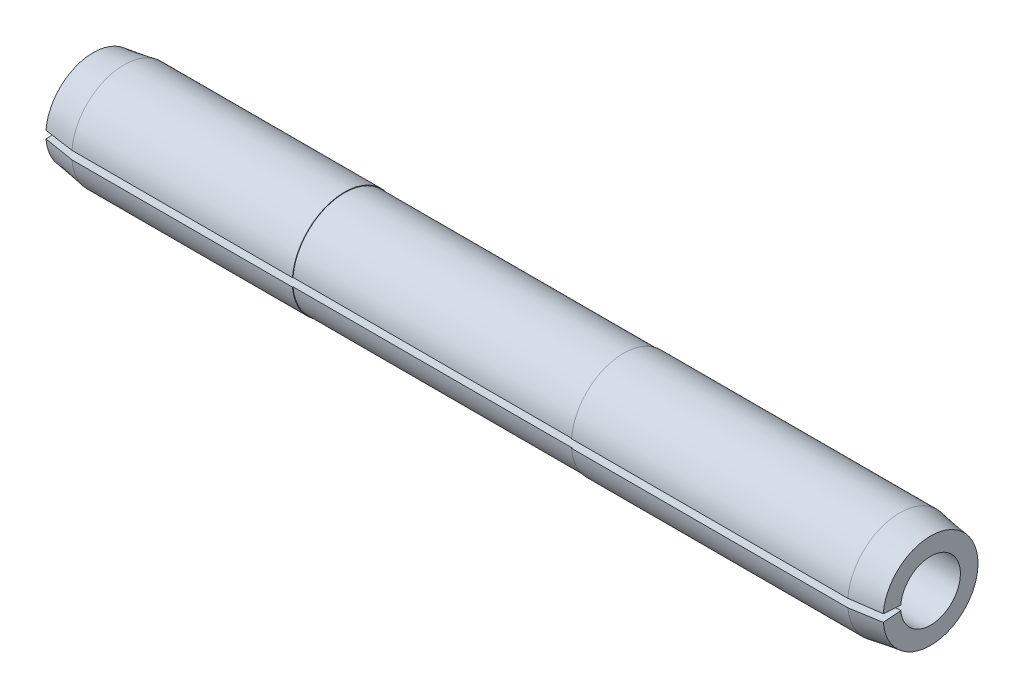
SolidWorks part; units mm, degrees
material "Plain Carbon Steel"
ref_plane "Plane1" through (0, 0, 0) normal (0, 0, 1) x (1, 0, 0)
ref_plane "Plane2" through (0, 0, 0) normal (0, 1, 0) x (1, 0, 0)
ref_plane "Plane3" through (0, 0, 0) normal (1, 0, 0) x (0, 0, -1)
sketch "Sketch1" plane through (0, 0, 0) normal (0, 0, 1) x (1, 0, 0)
  line L0 (-9.525, 0) -> (111.125, 0) construction
  line L1 (0, 1.3589) -> (38.1, 1.3589)
  line L2 (38.1, 1.3589) -> (38.1, 2.159)
  line L3 (38.1, 2.159) -> (36.703, 2.3749)
  line L4 (36.703, 2.3749) -> (1.397, 2.3749)
  line L5 (1.397, 2.3749) -> (0, 2.159)
  line L7 (0, 2.159) -> (0, 1.3589)
  dimension "Diameter" = 4.7498
  dimension "Length" = 38.1
  dimension "Thickness" = 1.016
  dimension "Top_ch_len" = 1.397
  dimension "Bottom_ch_len" = 1.397
  dimension "Bottom_ch_dia" = 4.318
  dimension "Top_ch_dia" = 4.318
revolve "Base-Revolve" add sketch "Sketch1" angle 360 about L0
sketch "Sketch2" plane through (0, 0, 0) normal (-1, 0, 0) x (0, -1, 0)
  line L0 (0, 0) -> (0.1901, 2.4149)
  line L1 (0, -3.175) -> (0, 12.7) construction
  line L2 (0, 0) -> (-0.1901, 2.4149)
  arc A0 (0.1901, 2.4149) -> (-0.1901, 2.4149) centre (0, 0) ccw
  dimension "D1" = 2.4224
  dimension "Gap_ang" = 9
extrude "Gap" cut sketch "Sketch2" against normal through all
ref_plane "center Plane4" through (17.78, 0, 0) normal (1, 0, 0) x (0, 0, -1)
sketch "Sketch3" plane through (17.78, 0, 0) normal (1, 0, 0) x (0, 0, -1)
  circle A0 centre (0, 0) radius 2.3495
  circle A1 centre (0, 0) radius 4.9284
  dimension "D1" = 4.699
extrude "Cut-Extrude1" cut sketch "Sketch3" against normal blind 6.35 and the other way blind 6.35
equation "\"D1@Sketch2\" = \"Diameter@Sketch1\" * 0.51"
equation "' \"Bottom_ch_dia@Sketch1\" = \"Diameter@Sketch1\" -  ( \"Thickness@Sketch1\" / 2 ) "
equation "' \"Top_ch_dia@Sketch1\" = \"Bottom_ch_dia@Sketch1\""
equation "' \"Top_ch_len@Sketch1\" = \"Bottom_ch_len@Sketch1\""
